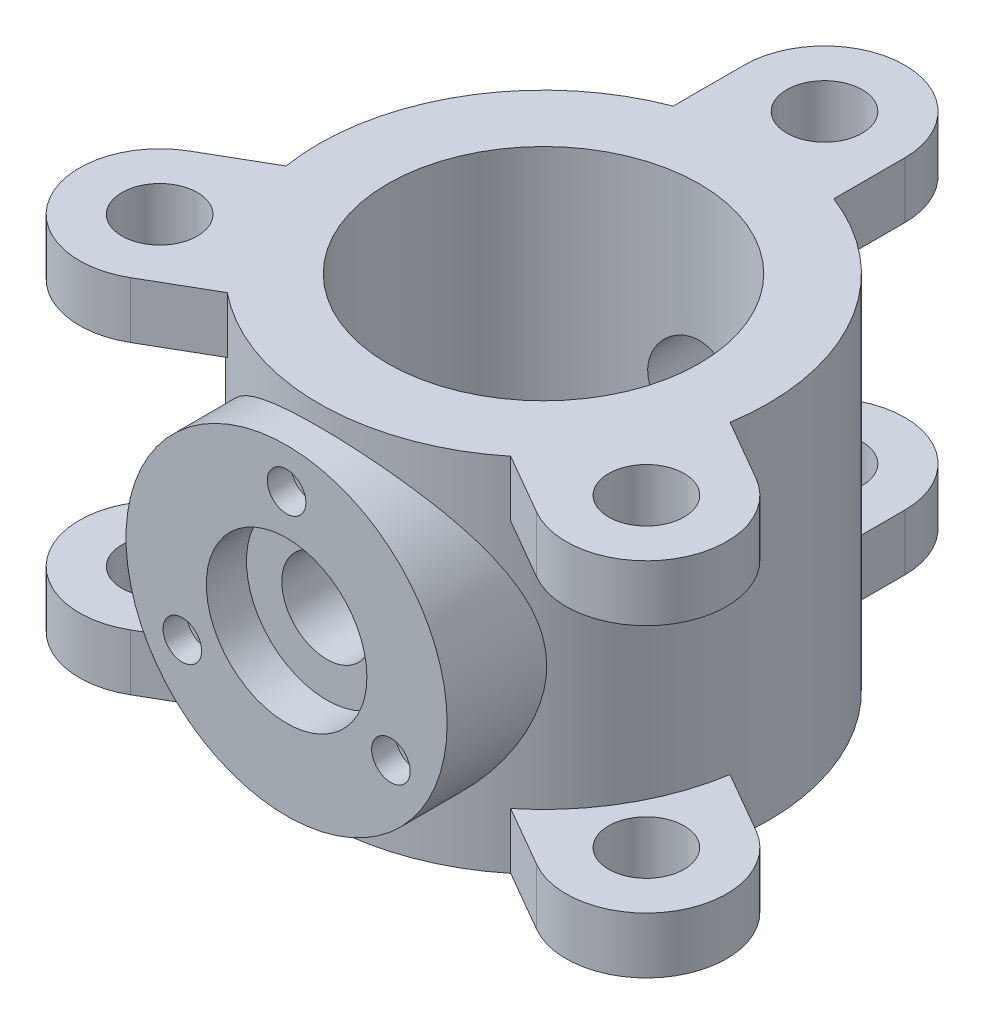
SolidWorks part; units mm, degrees
ref_plane "Front Plane" through (0, 0, 0) normal (0, 0, 1) x (1, 0, 0)
ref_plane "Top Plane" through (0, 0, 0) normal (0, 1, 0) x (1, 0, 0)
ref_plane "Right Plane" through (0, 0, 0) normal (1, 0, 0) x (0, 0, -1)
sketch "Sketch1" plane through (0, 0, 0) normal (0, 1, 0) x (1, 0, 0)
  line L0 (0, -160.269) -> (0, 160.3708) construction
  line L1 (-205.4578, 0) -> (209.9258, 0) construction
  circle A0 centre (0, 0) radius 97
  circle A10 centre (0, 0) radius 140
  point P28 (0, 0)
  dimension "D1" = 194
  dimension "D2" = 280
extrude "Boss-Extrude7" add sketch "Sketch1" along normal blind 225
sketch "Sketch4" plane through (0, 225, 0) normal (0, 1, 0) x (1, 0, 0)
  line L0 (50, 175) -> (50, 130.767)
  line L1 (-50, 175) -> (50, 175) construction
  line L5 (50, 130.767) -> (-50, 130.767)
  line L6 (-50, 130.767) -> (-50, 175)
  arc A0 (50, 175) -> (-50, 175) centre (0, 175) ccw
  circle A1 centre (0, 0) radius 140 construction
  circle A2 centre (0, 175) radius 23.5
  dimension "D2" = 100
  dimension "D3" = 47
  dimension "D1" = 175
extrude "Boss-Extrude8" add sketch "Sketch4" against normal blind 35
pattern_circular "CirPattern1" count 3 over 360 about axis through (0, 0, 0) along (0, 1, 0) of "Boss-Extrude8"
ref_plane "Plane1" through (0, 112.5, 0) normal (0, 1, 0) x (1, 0, 0)
mirror "Mirror2" about plane through (0, 112.5, 0) normal (0, 1, 0) of "CirPattern1", "Boss-Extrude8"
ref_plane "Plane2" through (0, 0, 160) normal (0, 0, 1) x (1, 0, 0)
sketch "Sketch6" plane through (0, 0, 160) normal (0, 0, 1) x (1, 0, 0)
  line L0 (-88.2475, 0) -> (88.2475, 0) construction
  circle A0 centre (0, 112.5) radius 100
  point P2 (0, 0)
  dimension "D1" = 200
  dimension "D2" = 112.5
extrude "Boss-Extrude9" add sketch "Sketch6" against normal up to next
sketch "Sketch7" plane through (0, 0, 160) normal (0, 0, 1) x (1, 0, 0)
  circle A0 centre (0, 112.5) radius 50
  dimension "D1" = 100
extrude "Cut-Extrude1" cut sketch "Sketch7" against normal blind 25 contours A0
sketch "Sketch8" plane through (0, 0, 135) normal (0, 0, 1) x (1, 0, 0)
  circle A0 centre (0, 112.5) radius 28
  dimension "D1" = 56
extrude "Cut-Extrude2" cut sketch "Sketch8" against normal through all
sketch "Sketch9" plane through (0, 0, 160) normal (0, 0, 1) x (1, 0, 0)
  circle A0 centre (0, 187.5) radius 12
  circle A1 centre (0, 112.5) radius 50 construction
  point P4 (0, 0)
  dimension "D1" = 24
  dimension "D2" = 75
extrude "Cut-Extrude3" cut sketch "Sketch9" against normal blind 15
pattern_circular "CirPattern4" count 3 over 360 about axis through (0, 112.5, 0) along (0, 0, 1) of "Cut-Extrude3"
